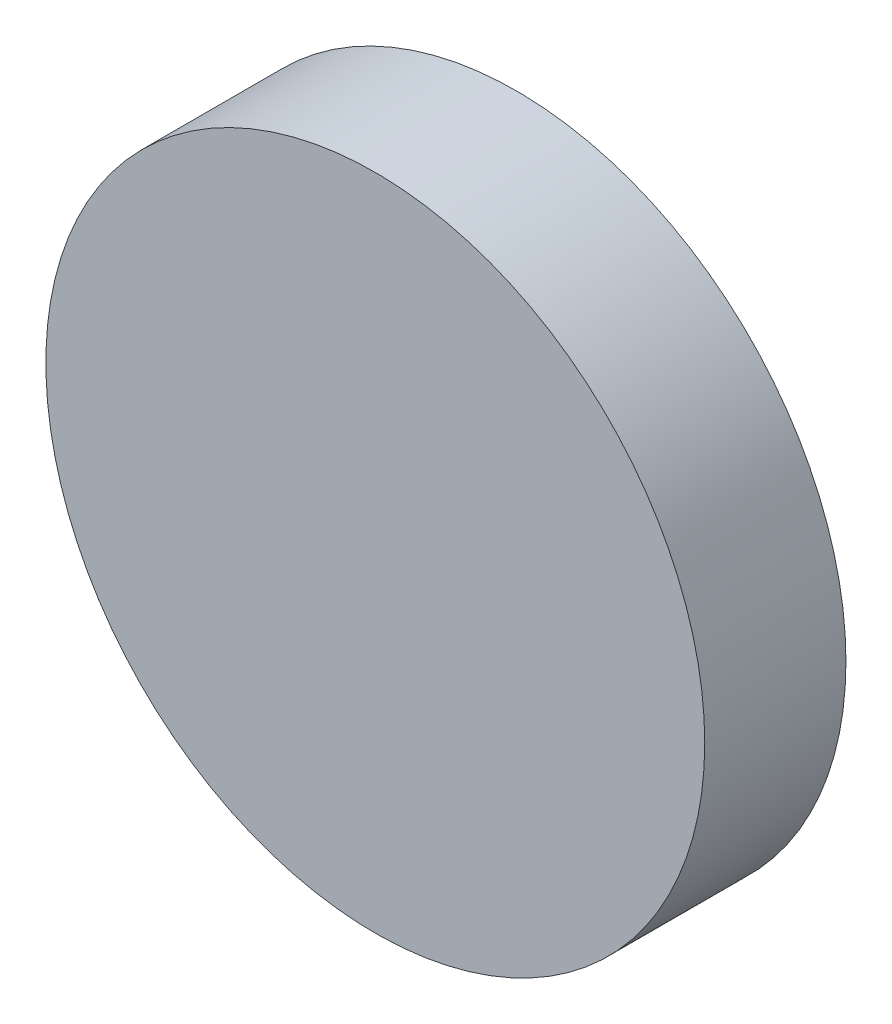
SolidWorks part; units mm, degrees
ref_plane "Front Plane" through (0, 0, 0) normal (0, 0, 1) x (1, 0, 0)
ref_plane "Top Plane" through (0, 0, 0) normal (0, 1, 0) x (1, 0, 0)
ref_plane "Right Plane" through (0, 0, 0) normal (1, 0, 0) x (0, 0, -1)
sketch "Sketch1" plane through (0, 0, 0) normal (0, 0, 1) x (1, 0, 0)
  circle A0 centre (0, 0) radius 140
  dimension "D1" = 280
extrude "Boss-Extrude1" add sketch "Sketch1" along normal blind 60
